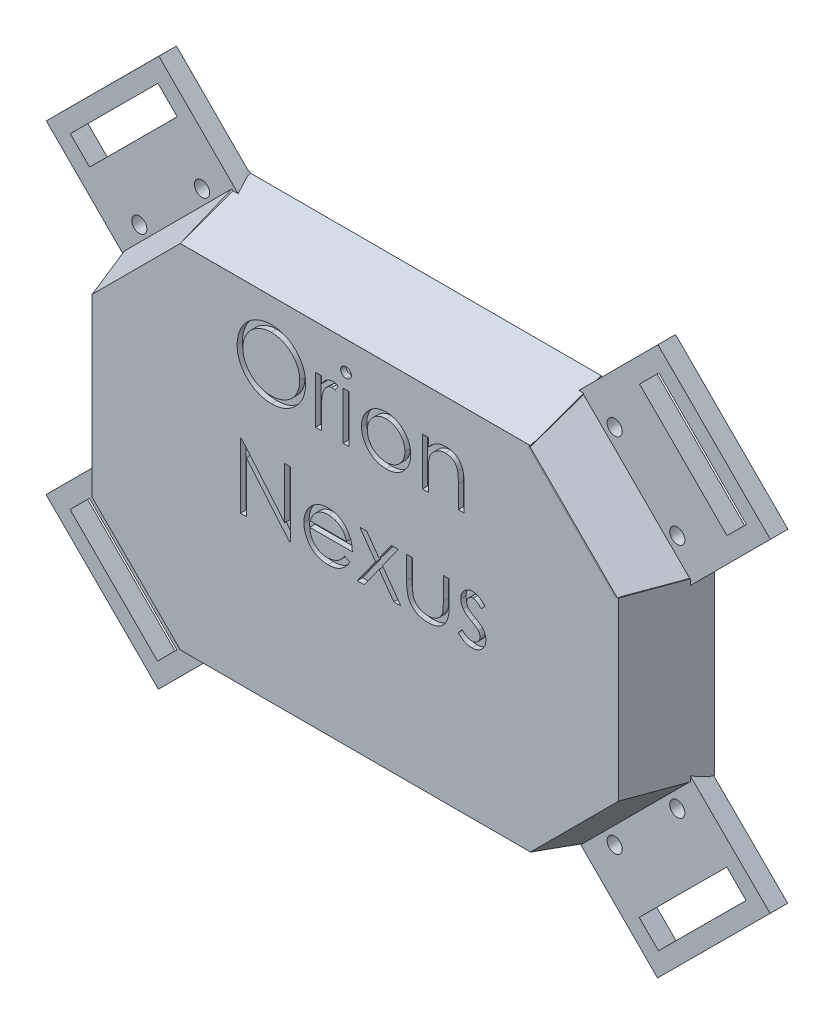
SolidWorks part; units mm, degrees
ref_plane "Alzado" through (0, 0, 0) normal (0, 0, 1) x (1, 0, 0)
ref_plane "Planta" through (0, 0, 0) normal (0, 1, 0) x (1, 0, 0)
ref_plane "Vista lateral" through (0, 0, 0) normal (1, 0, 0) x (0, 0, -1)
sketch "Croquis1" plane through (0, 0, 0) normal (0, 0, 1) x (1, 0, 0)
  line L0 (-75, 25) -> (-100, 0)
  line L1 (-75, -75) -> (24.5086, -75)
  line L2 (-100, -50) -> (-100, 0)
  line L3 (-75, 25) -> (24.5086, 25)
  line L4 (49.5086, -50) -> (49.5086, 0)
  line L5 (-100, -75) -> (49.5086, 37.1315) construction
  line L6 (-100, 25) -> (142.5356, -35.6339) construction
  line L7 (-100, -50) -> (-75, -75)
  line L8 (-25.2457, -142.755) -> (-25.2457, 104.8865) construction
  line L9 (49.5086, -50) -> (24.5086, -75)
  line L10 (24.5086, 25) -> (49.5086, 0)
  point P0 (0, 0)
  point P13 (-25.2457, -18.9343)
  dimension "D1" = 150
  dimension "D2" = 100
  dimension "D3" = 25
  dimension "D4" = 25
  dimension "D5" = 25
  dimension "D6" = 25
extrude "Saliente-Extruir1" add sketch "Croquis1" along normal blind 3
ref_plane "Plano1" through (-89.2664, 0, 32.4903) normal (0.9397, 0, -0.342) x (0, -1, 0)
sketch "Croquis2" plane through (-89.2664, 0, 32.4903) normal (0.9397, 0, -0.342) x (0, -1, 0)
  line L0 (-114.3661, -48.7501) -> (114.3661, 48.7501) construction
  line L2 (-35.6339, 48.7501) -> (35.6339, -48.7501) construction
  line L3 (-35.6339, 48.7501) -> (114.3661, 48.7501) construction
  line L4 (49.9969, 31.3828) -> (-0.0414, 31.3828)
  line L5 (-0.0414, 31.3828) -> (-0.0414, 65.9501)
  line L6 (-0.0414, 65.9501) -> (49.9969, 65.9501)
  line L7 (49.9969, 65.9501) -> (49.9969, 31.3828)
  point P4 (0, 0)
  point P10 (0, 0)
extrude "Saliente-Extruir2" add sketch "Croquis2" along normal blind 3 separate body
ref_plane "Plano2" through (44.6814, 0, 16.2627) normal (-0.9397, 0, -0.342) x (0, 1, 0)
ref_plane "Plano3" through (0, -67.1908, 24.4555) normal (0, 0.9397, -0.342) x (1, 0, 0)
sketch "Croquis3" plane through (44.6814, 0, 16.2627) normal (-0.9397, 0, -0.342) x (0, 1, 0)
  line L0 (-49.9938, 14.1271) -> (-0.0164, 14.1271)
  line L1 (-49.9938, 14.1271) -> (-49.9938, 39.1271)
  line L2 (-0.0164, 14.1271) -> (-0.0164, 39.1271)
  line L3 (-49.9938, 39.1271) -> (-0.0164, 39.1271)
  line L4 (-50, 16.9329) -> (0, 16.9329) construction
  dimension "D1" = 25
extrude "Saliente-Extruir3" add sketch "Croquis3" along normal blind 3 separate body
ref_plane "Plano4" through (0, 23.0397, 8.3858) normal (0, -0.9397, -0.342) x (-1, 0, 0)
ref_plane "Plano5" through (23.8356, 23.8356, 8.2859) normal (-0.6867, -0.6867, -0.2387) x (-0.7071, 0.7071, 0)
sketch "Croquis4" plane through (0, -67.1908, 24.4555) normal (0, 0.9397, -0.342) x (1, 0, 0)
  line L0 (-75, 22.8326) -> (24.4746, 22.8326)
  line L1 (-75, 22.8326) -> (-75, 54.0193)
  line L2 (24.4746, 22.8326) -> (24.4746, 54.0193)
  line L3 (-75, 54.0193) -> (24.4746, 54.0193)
extrude "Saliente-Extruir4" add sketch "Croquis4" along normal blind 3
sketch "Croquis5" plane through (0, 23.0397, 8.3858) normal (0, -0.9397, -0.342) x (-1, 0, 0)
  line L1 (75.0002, 5.7427) -> (-24.6223, 5.7427)
  line L2 (75.0002, 5.7427) -> (75.0002, 56.0507)
  line L3 (75.0002, 56.0507) -> (-24.6223, 56.0507)
  line L4 (-24.6223, 5.7427) -> (-24.6223, 56.0507)
extrude "Saliente-Extruir5" add sketch "Croquis5" along normal blind 3
sketch "Croquis6" plane through (23.8356, 23.8356, 8.2859) normal (-0.6867, -0.6867, -0.2387) x (-0.7071, 0.7071, 0)
  line L0 (-34.8048, 5.2586) -> (0.3599, 5.2586)
  line L1 (0.3599, 5.2586) -> (12.0713, 54.417)
  line L2 (80.8869, 37.9905) -> (10.4431, 54.8057) construction
  line L3 (12.0713, 54.417) -> (-47.2315, 54.417)
  line L4 (-47.2315, 54.417) -> (-34.8048, 5.2586)
  point P0 (-35.1901, 25.1244)
  point P2 (0, 25.1244)
extrude "Saliente-Extruir6" add sketch "Croquis6" along normal blind 3
ref_plane "Plano6" through (-69.8639, -69.8639, 28.3311) normal (0.6797, 0.6797, -0.2756) x (0.7071, -0.7071, 0)
sketch "Croquis10" plane through (-69.8639, -69.8639, 28.3311) normal (0.6797, 0.6797, -0.2756) x (0.7071, -0.7071, 0)
  line L0 (0, 26.3522) -> (-35.3553, 26.352)
  line L1 (-35.3553, 26.352) -> (-44.3611, 60.232)
  line L2 (-44.3611, 60.232) -> (6.8397, 57.8359)
  line L3 (6.8397, 57.8359) -> (0, 26.3522)
extrude "Saliente-Extruir7" add sketch "Croquis10" along normal blind 3
ref_plane "Plano7" through (47.261, -47.261, 16.9248) normal (-0.6855, 0.6855, -0.2455) x (0.7071, 0.7071, 0)
sketch "Croquis11" plane through (47.261, -47.261, 16.9248) normal (-0.6855, 0.6855, -0.2455) x (0.7071, 0.7071, 0)
  line L0 (-0.3475, 14.3643) -> (-35.8186, 14.3643)
  line L1 (-35.8186, 14.3643) -> (-43.2899, 45.0598)
  line L2 (-43.2899, 45.0598) -> (6.8659, 43.7297)
  line L4 (-17.0659, 14.3643) -> (-17.0659, 44.3643) construction
  line L5 (-0.3475, 14.3643) -> (6.8659, 43.7297)
  dimension "D1" = 30
extrude "Saliente-Extruir8" add sketch "Croquis11" along normal blind 3
ref_plane "Plano8" through (-46.7633, 46.7633, 18.9634) normal (0.6797, -0.6797, -0.2756) x (-0.7071, -0.7071, 0)
sketch "Croquis12" plane through (-46.7633, 46.7633, 18.9634) normal (0.6797, -0.6797, -0.2756) x (-0.7071, -0.7071, 0)
  line L0 (35.3553, 16.6067) -> (70.7101, 16.6067)
  line L1 (70.7101, 16.6067) -> (79.3389, 50.2211)
  line L2 (79.3389, 50.2211) -> (27.7199, 47.8811)
  line L3 (27.7199, 47.8811) -> (35.3553, 16.6067)
extrude "Saliente-Extruir9" add sketch "Croquis12" along normal blind 3
sketch "Croquis13" plane through (0, 0, 0) normal (0, 1, 0) x (1, 0, 0)
  line L0 (-25.2834, -2.9894) -> (-25.2834, 17.0106) construction
  line L1 (24.4333, -2.9894) -> (-75.0001, -2.9894) construction
  line L3 (-153.5047, 84.2689) -> (102.9379, 84.2689)
  line L4 (-153.5047, 84.2689) -> (-153.5047, 17.0106)
  line L5 (-153.5047, 17.0106) -> (102.9379, 17.0106)
  line L6 (102.9379, 84.2689) -> (102.9379, 17.0106)
  dimension "D1" = 20
extrude "Cortar-Extruir1" cut sketch "Croquis13" against normal through all both and the other way through all
ref_plane "Plano11" through (0, 0, -17.0106) normal (0, 0, -1) x (-1, 0, 0)
sketch "Croquis14" plane through (0, 0, -17.0106) normal (0, 0, -1) x (-1, 0, 0)
  line L0 (-54.6912, -1.9629) -> (-22.7541, 29.9742)
  line L1 (-54.6912, -1.9629) -> (-77.6722, 21.0181)
  line L2 (-22.7541, 29.9742) -> (-45.735, 52.9552)
  line L3 (-77.6722, 21.0181) -> (-45.735, 52.9552)
  line L4 (-42.4518, 49.672) -> (-74.3889, 17.7348)
  line L5 (-36.9654, 44.1856) -> (-68.9025, 12.2485)
  line L6 (-70.8534, 21.2704) -> (-65.367, 15.784)
  line L7 (-45.9873, 46.1364) -> (-40.501, 40.6501)
  line L8 (-56.3535, -25.0051) -> (107.2833, -24.8758) construction
  line L9 (-24.6223, 31.8425) -> (-56.6277, -0.1629) construction
  line L10 (107.2833, -49.5516) -> (107.2833, -0.2001) construction
  line L11 (25.1889, 32.2833) -> (25.2627, -82.2833) construction
  line L12 (-24.6223, 32.2833) -> (75.0002, 32.2833) construction
  line L13 (-24.4746, -82.2833) -> (75, -82.2833) construction
  line L14 (96.3473, 46.2281) -> (90.868, 40.7346)
  line L15 (92.8072, 49.759) -> (124.7855, 17.8631)
  line L16 (121.2454, 21.3941) -> (115.7661, 15.9006)
  line L17 (87.3279, 44.2656) -> (119.3061, 12.3696)
  line L18 (73.4545, 30.3564) -> (96.0862, 53.0465)
  line L19 (128.0645, 21.1505) -> (96.0862, 53.0465)
  line L20 (105.4327, -1.5396) -> (128.0645, 21.1505)
  line L21 (105.4327, -1.5396) -> (73.4545, 30.3564)
  line L22 (105.5635, -48.3088) -> (73.6357, -80.2553)
  line L23 (105.5635, -48.3088) -> (128.1372, -70.8693)
  line L24 (128.1372, -70.8693) -> (96.2094, -102.8157)
  line L25 (73.6357, -80.2553) -> (96.2094, -102.8157)
  line L26 (121.3185, -71.1236) -> (115.8305, -65.6388)
  line L27 (96.4597, -95.9969) -> (90.9717, -90.5121)
  line L28 (92.9252, -99.5335) -> (124.853, -67.587)
  line L29 (87.4372, -94.0487) -> (119.365, -62.1022)
  line L30 (-22.6672, -79.9313) -> (-45.6119, -102.9485)
  line L31 (-77.5994, -71.0619) -> (-45.6119, -102.9485)
  line L32 (-54.4888, -48.1071) -> (-77.5994, -71.0619)
  line L33 (-54.4888, -48.1071) -> (-22.6672, -79.9313)
  line L34 (-45.8749, -96.1302) -> (-40.3972, -90.6351)
  line L35 (-70.7802, -71.3035) -> (-65.3025, -65.8084)
  line L36 (-42.3338, -99.6601) -> (-74.3214, -67.7735)
  line L37 (-36.8561, -94.1651) -> (-68.8437, -62.2785)
  dimension "D1" = 4.6432
  dimension "D2" = 7.7589
  dimension "D3" = 32.5
  dimension "D4" = 5
  dimension "D5" = 5
extrude "Saliente-Extruir12" add sketch "Croquis14" against normal blind 5 contours L2 L5 L1 L0 | L6 L4 L1 L5 | L4 L2 L3 L1 | L4 L7 L5 L2 | L37 L30 L33 L32 | L35 L37 L32 L36 | L30 L36 L32 L31 | L30 L37 L34 L36 | L29 L26 L28 L23 | L28 L25 L24 L23 | L25 L29 L23 L22 | L29 L25 L28 L27 | L21 L20 L17 L18 | L18 L17 L14 L15 | L15 L20 L19 L18 | L17 L20 L15 L16
sketch "Croquis15" plane through (0, 0, 0) normal (0, 0, -1) x (-1, 0, 0)
  line L0 (-56.0979, -24.8758) -> (107.2833, -24.8758) construction
  line L1 (-28.4287, 2.9613) -> (4.5627, 2.9613)
  line L2 (-28.4287, 2.9613) -> (-28.4287, -53.0235)
  line L3 (-28.4287, -53.0235) -> (4.5477, -53.0235)
  line L5 (13.3919, 3.1242) -> (46.6477, 3.1242)
  line L7 (13.3834, -52.8758) -> (46.6477, -52.8758)
  line L8 (46.6477, 3.1242) -> (46.6477, -52.8758)
  line L10 (107.2833, -49.5516) -> (107.2833, -0.2001) construction
  line L11 (-28.4287, -53.0235) -> (4.5627, 2.9613) construction
  line L12 (-28.4287, 2.9613) -> (4.5477, -53.0235) construction
  line L13 (13.3919, 3.1242) -> (46.6477, -52.8758) construction
  line L14 (14.966, -50.4449) -> (46.6477, -5.5621) construction
  line L15 (3.0713, -51.5387) -> (4.5477, -53.0235)
  line L16 (-26.9287, -51.5387) -> (3.0713, -51.5387)
  line L17 (-26.9287, -51.5387) -> (-26.9287, 1.4613)
  line L18 (-26.9287, 1.4613) -> (3.0542, 1.4613)
  line L20 (-26.9287, -51.5387) -> (3.0542, 1.4613) construction
  line L21 (-26.9287, 1.4613) -> (3.0713, -51.5387) construction
  line L22 (9.8834, -51.3758) -> (44.8834, -51.3758)
  line L24 (14.8834, 1.6242) -> (44.8834, 1.6242)
  line L25 (44.8834, -51.3758) -> (44.8834, 1.6242)
  line L26 (9.8834, -51.3758) -> (44.8834, 1.6242) construction
  line L27 (14.8834, 1.6242) -> (44.8834, -51.3758) construction
  line L28 (3.0542, 1.4613) -> (4.5627, 2.9613)
  line L29 (13.3919, 3.1242) -> (14.8834, 1.6242)
  line L30 (9.8834, -51.3758) -> (13.3834, -52.8758)
  point P15 (46.6477, -24.8758)
  point P16 (-11.933, -25.0311)
  point P22 (28.7296, -22.8374)
  dimension "D1" = 1.5
  dimension "D2" = 1.5
  dimension "D3" = 1.5
  dimension "D4" = 1.5
  dimension "D5" = 53
  dimension "D6" = 30
  dimension "D7" = 53
  dimension "D8" = 35
extrude "Saliente-Extruir14" add sketch "Croquis15" along normal blind 15
sketch "Croquis16" plane through (0, 0, 3) normal (0, 0, 1) x (1, 0, 0)
  text T0 "Orion \r\nNexus" font "Century Gothic" height 18.5
extrude "Cortar-Extruir2" cut sketch "Croquis16" against normal blind 1.5
sketch "Croquis17" plane through (0, 0, -17.0106) normal (0, 0, -1) x (-1, 0, 0)
  line L0 (76.735, 33.6454) -> (113.8164, -3.3406) construction
  line L1 (73.5612, 30.4634) -> (96.0862, 53.0465) construction
  line L2 (113.523, -56.2637) -> (81.5952, -88.2101) construction
  line L3 (105.5635, -48.3088) -> (128.1372, -70.8693) construction
  line L4 (73.844, -80.4634) -> (96.2094, -102.8157) construction
  line L5 (-31.6984, 38.9186) -> (-63.6355, 6.9814) construction
  line L6 (-23.2432, 30.4634) -> (-45.735, 52.9552) construction
  line L7 (-54.972, -1.682) -> (-77.6722, 21.0181) construction
  line L8 (-62.7007, -56.2637) -> (-30.787, -88.0767) construction
  line L9 (-54.972, -48.587) -> (-77.5994, -71.0619) construction
  line L10 (-23.1977, -80.4634) -> (-45.6119, -102.9485) construction
  line L11 (105.4634, -1.5088) -> (128.0645, 21.1505) construction
  line L14 (90.868, 40.7346) -> (115.7661, 15.9006) construction
  line L15 (25.1889, 32.2833) -> (25.2627, -82.2833) construction
  line L16 (-24.6223, 32.2833) -> (75.0002, 32.2833) construction
  line L17 (-24.4746, -82.2833) -> (75, -82.2833) construction
  line L18 (107.2833, -24.8758) -> (-56.3535, -24.8758) construction
  line L19 (107.2833, -49.5516) -> (107.2833, -0.2001) construction
  circle A0 centre (101.633, 8.8114) radius 2.15
  circle A1 centre (83.8152, 26.5834) radius 2.15
  circle A2 centre (-33.4299, 26.5079) radius 2.15
  circle A3 centre (-51.2249, 8.7129) radius 2.15
  circle A4 centre (83.8152, -76.335) radius 2.15
  circle A5 centre (101.633, -58.563) radius 2.15
  circle A6 centre (-51.2249, -58.4646) radius 2.15
  circle A7 centre (-33.4299, -76.2596) radius 2.15
  dimension "D1" = 4.3
  dimension "D2" = 4.3
  dimension "D3" = 10
  dimension "D4" = 10
  dimension "D5" = 15
extrude "Cortar-Extruir3" cut sketch "Croquis17" against normal blind 13
